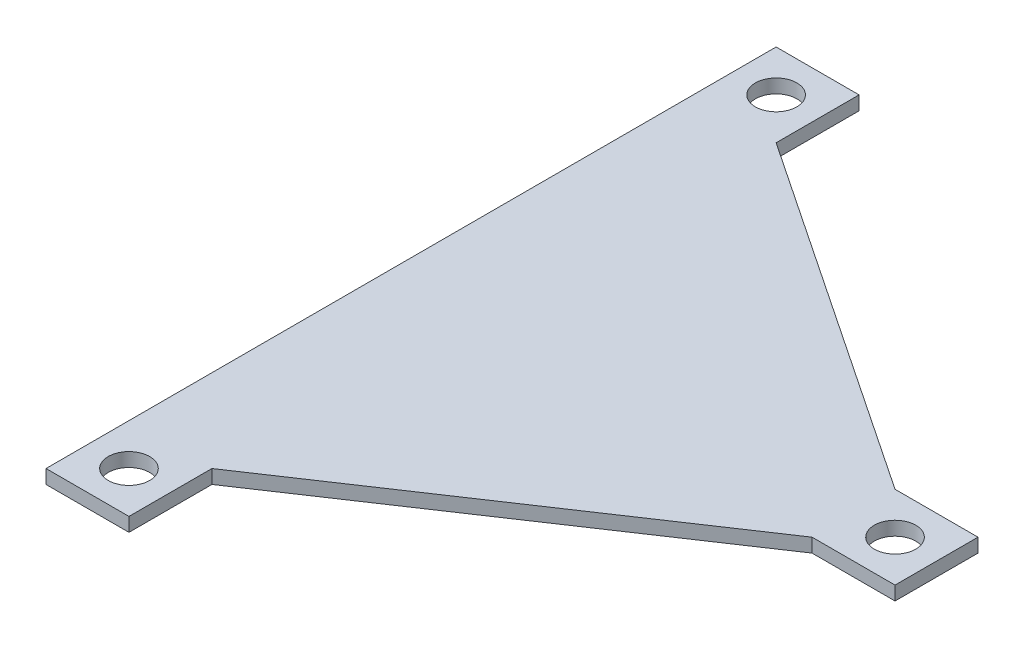
SolidWorks part; units mm, degrees
ref_plane "Front Plane" through (0, 0, 0) normal (0, 0, 1) x (1, 0, 0)
ref_plane "Top Plane" through (0, 0, 0) normal (0, 1, 0) x (1, 0, 0)
ref_plane "Right Plane" through (0, 0, 0) normal (1, 0, 0) x (0, 0, -1)
sketch "Croquis1" plane through (0, 0, 0) normal (0, 1, 0) x (1, 0, 0)
  line L0 (-3, 3) -> (-3, -49.8)
  line L1 (-3, -49.8) -> (3, -49.8)
  line L2 (3, -49.8) -> (3, -43.8)
  line L3 (3, -43.8) -> (29, -26.4)
  line L4 (29, -26.4) -> (35, -26.4)
  line L5 (35, -26.4) -> (35, -20.4)
  line L6 (35, -20.4) -> (29, -20.4)
  line L7 (29, -20.4) -> (3, -3)
  line L8 (3, -3) -> (3, 3)
  line L9 (3, 3) -> (-3, 3)
  circle A0 centre (0, 0) radius 1.5
  circle A1 centre (0, -46.8) radius 1.5
  circle A2 centre (32, -23.4) radius 1.5
  dimension "D1" = 3
  dimension "D2" = 46.8
  dimension "D3" = 32
  dimension "D4" = 23.4
  dimension "D5" = 3
  dimension "D6" = 3
  dimension "D8" = 3
  dimension "D9" = 3
  dimension "D11" = 3
  dimension "D7" = 6
  dimension "D14" = 6
  dimension "D12" = 6
  dimension "D13" = 6
  dimension "D15" = 6
  dimension "D10" = 6
extrude "Saliente-Extruir1" add sketch "Croquis1" along normal blind 1
sketch "Croquis2" plane through (0, 4, 0) normal (0, 1, 0) x (1, 0, 0)
  line L0 (29, -20.4) -> (29, -26.4)
  line L1 (29, -26.4) -> (1.3789, -65.1957)
  line L2 (1.3789, -65.1957) -> (-23.2695, -18.4165)
  line L3 (-23.2695, -18.4165) -> (-7.6301, 16.3281)
  line L4 (-7.6301, 16.3281) -> (29, -20.4)
extrude "Cortar-Extruir1" cut sketch "Croquis2" against normal blind 1
equation "\"D4@Croquis1\"=\"D2@Croquis1\"/2"
